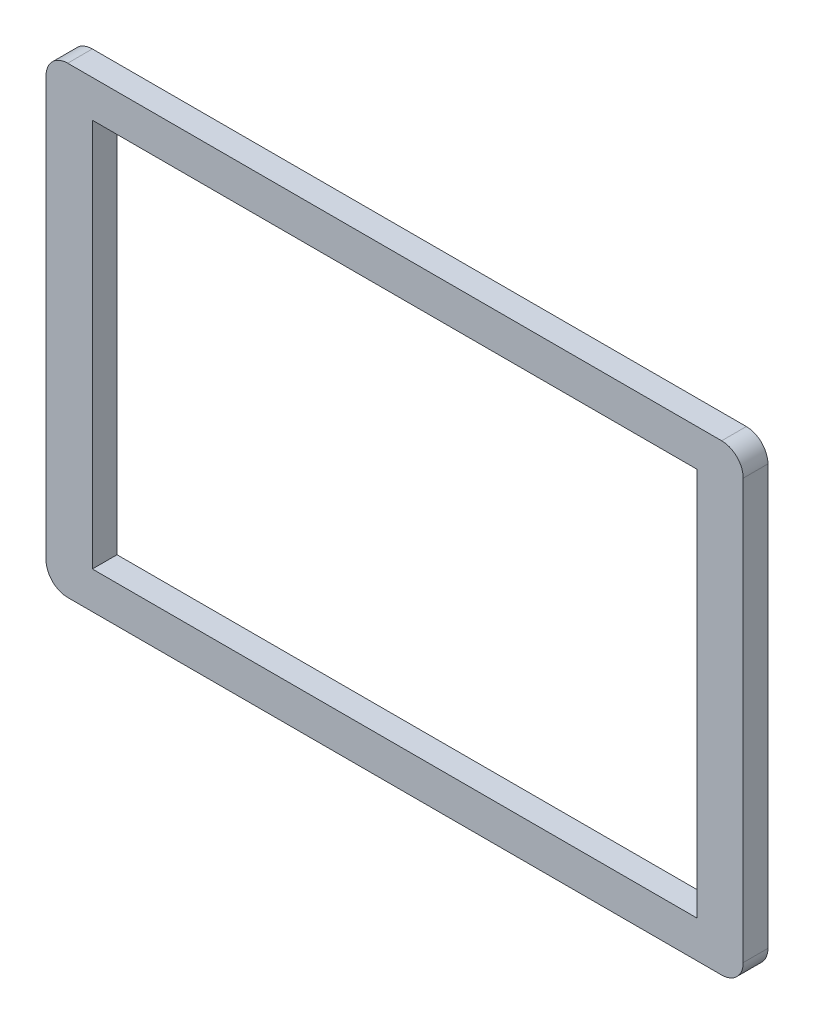
SolidWorks part; units mm, degrees
ref_plane "Front Plane" through (0, 0, 0) normal (0, 0, 1) x (1, 0, 0)
ref_plane "Top Plane" through (0, 0, 0) normal (0, 1, 0) x (1, 0, 0)
ref_plane "Right Plane" through (0, 0, 0) normal (1, 0, 0) x (0, 0, -1)
sketch "Sketch1" plane through (0, 0, 0) normal (0, 0, 1) x (1, 0, 0)
  line L1 (-82.521, 40.8431) -> (30.479, 40.8431)
  line L2 (-82.521, 40.8431) -> (-82.521, -34.1569)
  line L3 (-82.521, -34.1569) -> (30.479, -34.1569)
  line L4 (30.479, 40.8431) -> (30.479, -34.1569)
  line L5 (-75.021, 34.8431) -> (22.979, 34.8431)
  line L6 (-75.021, 34.8431) -> (-75.021, -28.1569)
  line L7 (-75.021, -28.1569) -> (22.979, -28.1569)
  line L8 (22.979, 34.8431) -> (22.979, -28.1569)
  point P8 (-26.021, 34.8431)
  point P9 (-26.021, 40.8431)
  point P10 (-75.021, 3.3431)
  point P11 (-82.521, 3.3431)
  dimension "D1" = 75
  dimension "D2" = 113
  dimension "D3" = 98
  dimension "D4" = 63
  dimension "D5" = 0
extrude "Boss-Extrude1" add sketch "Sketch1" along normal blind 4
fillet "Fillet1" radius 3.5 4 edges at (-82.521, 40.8431, 2) (-82.521, -34.1569, 2) (30.479, -34.1569, 2) (30.479, 40.8431, 2)
